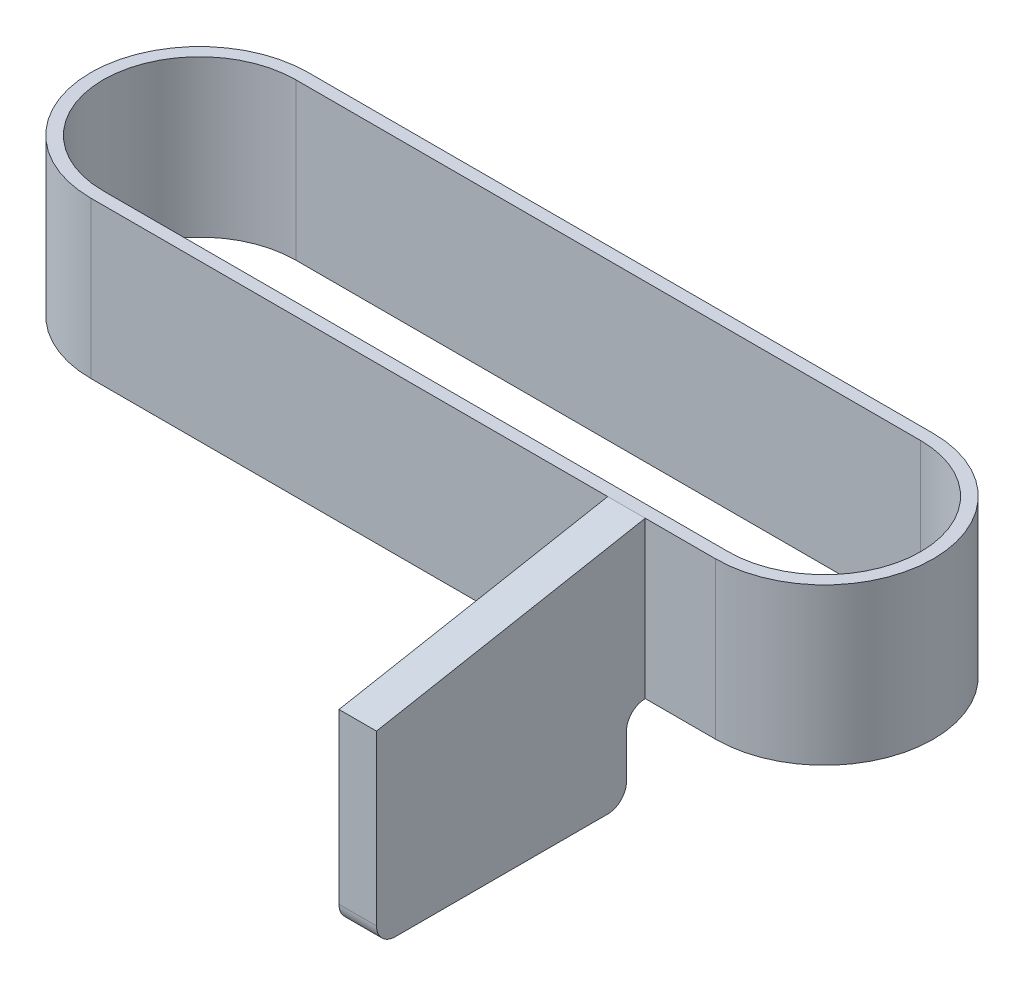
SolidWorks part; units mm, degrees
ref_plane "前视基准面" through (0, 0, 0) normal (0, 0, 1) x (1, 0, 0)
ref_plane "上视基准面" through (0, 0, 0) normal (0, 1, 0) x (1, 0, 0)
ref_plane "右视基准面" through (0, 0, 0) normal (1, 0, 0) x (0, 0, -1)
other "Configuration Table"
sketch "草图1" plane through (0, 0, 0) normal (0, 1, 0) x (1, 0, 0)
  line L0 (-50, 0) -> (50, 0) construction
  line L1 (-50, 15.4) -> (50, 15.4)
  line L2 (-50, -15.4) -> (50, -15.4)
  line L3 (-50, 0) -> (50, 0) construction
  line L4 (-50, 17.4) -> (50, 17.4)
  line L5 (-50, -17.4) -> (50, -17.4)
  arc A0 (-50, 15.4) -> (-50, -15.4) centre (-50, 0) ccw
  arc A1 (50, -15.4) -> (50, 15.4) centre (50, 0) ccw
  arc A2 (-50, 17.4) -> (-50, -17.4) centre (-50, 0) ccw
  arc A3 (50, -17.4) -> (50, 17.4) centre (50, 0) ccw
  point P2 (0, 0)
  point P10 (0, 0)
  dimension "D1" = 15.4
  dimension "D3" = 17.4
  dimension "D2" = 100
extrude "凸台-拉伸1" add sketch "草图1" along normal mid plane 25 contours A0 L2 A1 L1
sketch "草图2" plane through (0, 0, 17.4) normal (0, 0, 1) x (1, 0, 0)
  line L2 (27.5572, 12.5) -> (31.5572, 12.5)
  line L3 (31.5572, 12.5) -> (31.5572, -29.3598)
  line L5 (31.5572, -29.3598) -> (27.5572, -29.3598)
  line L6 (27.5572, -29.3598) -> (27.5572, 12.5)
  line M3 (-50, -12.5) -> (50, -12.5)
  line M5 (50, 12.5) -> (-50, 12.5)
  dimension "D2" = 4
extrude "凸台-拉伸2" [suppressed] add sketch "草图2" along normal blind 40 contours L6 L3 M3 M5 | L6 L3 L2 M5
sketch "草图3" [suppressed] plane through (0, 0, 17.4) normal (0, 0, -1) x (-1, 0, 0)
  line L1 (-31.5572, -12.5) -> (-27.5572, -12.5)
  line L2 (-31.5572, -12.5) -> (-31.5572, -29.3598)
  line L3 (-31.5572, -29.3598) -> (-27.5572, -29.3598)
  line L4 (-27.5572, -12.5) -> (-27.5572, -29.3598)
extrude "切除-拉伸1" [suppressed] cut sketch "草图3" against normal blind 3
sketch "草图4" plane through (0, 12.5, 0) normal (0, 1, 0) x (1, 0, 0)
  line L0 (38.7178, -17.4) -> (32.7178, -17.4)
  line L1 (-50, -17.4) -> (50, -17.4) construction
  line L2 (32.7178, -17.4) -> (32.7178, -60.4)
  line L3 (32.7178, -60.4) -> (38.7178, -60.4)
  line L4 (38.7178, -60.4) -> (38.7178, -17.4)
  dimension "D1" = 6
  dimension "D2" = 6
  dimension "D3" = 43
extrude "凸台-拉伸3" add sketch "草图4" against normal blind 38
sketch "草图5" plane through (0, 0, 17.4) normal (0, 0, -1) x (-1, 0, 0)
  line L1 (-38.7178, -12.5) -> (-32.7178, -12.5)
  line L2 (-38.7178, -12.5) -> (-38.7178, -25.5)
  line L3 (-38.7178, -25.5) -> (-32.7178, -25.5)
  line L4 (-32.7178, -12.5) -> (-32.7178, -25.5)
extrude "切除-拉伸2" cut sketch "草图5" against normal blind 3
sketch "草图6" plane through (0, 12.5, 0) normal (0, 1, 0) x (1, 0, 0)
  line L0 (32.7178, -17.4) -> (38.7178, -17.4)
  line L1 (38.7178, -17.4) -> (38.7178, -60.4)
  line L2 (38.7178, -60.4) -> (32.7178, -60.4)
  line L3 (32.7178, -60.4) -> (32.7178, -17.4)
extrude "切除-拉伸3" cut sketch "草图6" against normal blind 8
sketch "草图8" plane through (32.7178, 0, 0) normal (-1, 0, 0) x (0, 0, 1)
  line L0 (17.4, 12.5) -> (17.4, 4.5)
  line L1 (17.4, 4.5) -> (60.4, 4.5)
  line L2 (60.4, 4.5) -> (17.4, 12.5)
extrude "凸台-拉伸5" add sketch "草图8" against normal blind 6
fillet "圆角1" radius 3 2 edges at (35.7178, -25.5, 60.4) (35.7178, -25.5, 20.4)
fillet "圆角2" radius 3 1 edges at (35.7178, -12.5, 20.4)
